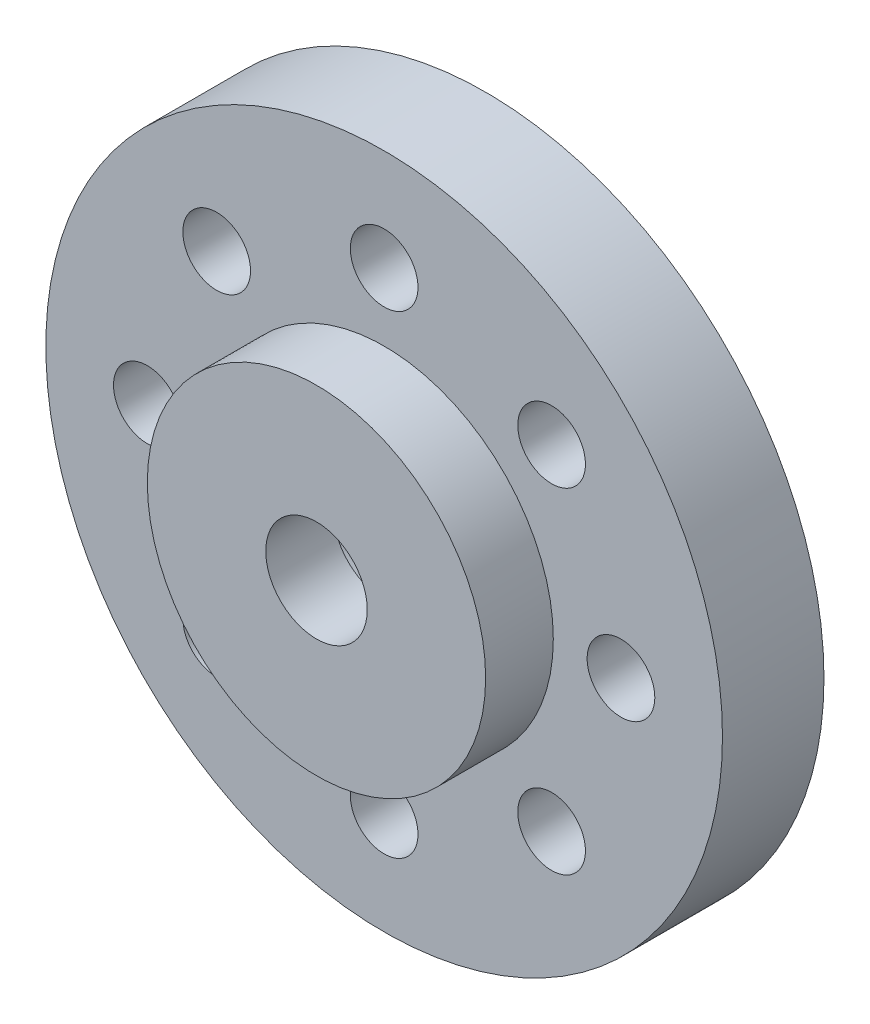
SolidWorks part; units mm, degrees
ref_plane "前视基准面" through (0, 0, 0) normal (0, 0, 1) x (1, 0, 0)
ref_plane "上视基准面" through (0, 0, 0) normal (0, 1, 0) x (1, 0, 0)
ref_plane "右视基准面" through (0, 0, 0) normal (1, 0, 0) x (0, 0, -1)
sketch "草图1" plane through (0, 0, 0) normal (0, 0, 1) x (1, 0, 0)
  circle A0 centre (0, 0) radius 10
  circle A1 centre (0, 0) radius 3
  circle A2 centre (7, 0) radius 1
  circle A3 centre (4.9497, -4.9497) radius 1
  circle A4 centre (0, -7) radius 1
  circle A5 centre (-4.9497, -4.9497) radius 1
  circle A6 centre (-7, 0) radius 1
  circle A7 centre (-4.9497, 4.9497) radius 1
  circle A8 centre (0, 7) radius 1
  circle A9 centre (4.9497, 4.9497) radius 1
  point P22 (0, 0)
  dimension "D1" = 20
  dimension "D2" = 6
  dimension "D3" = 2
  dimension "D4" = 7
  dimension "D5" = 8
extrude "凸台-拉伸1" add sketch "草图1" along normal blind 3
sketch "草图2" plane through (0, 0, 3) normal (0, 0, 1) x (1, 0, 0)
  circle A0 centre (0, 0) radius 5
  circle A1 centre (0, 0) radius 1.5
  dimension "D1" = 10
  dimension "D2" = 3
extrude "凸台-拉伸2" add sketch "草图2" along normal blind 2
